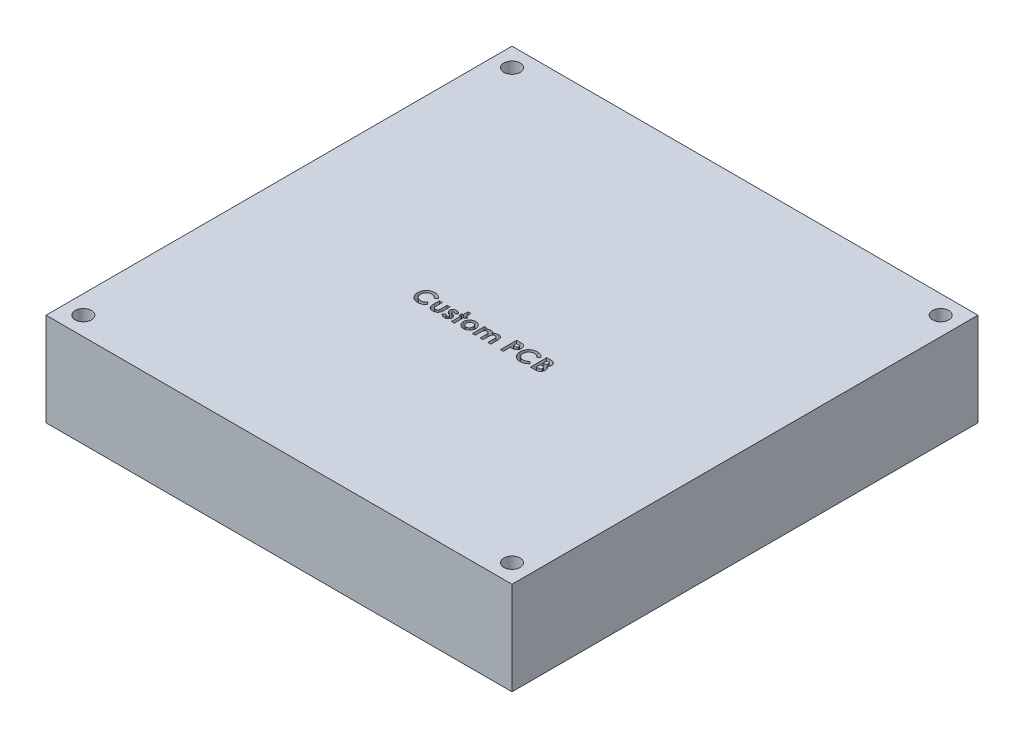
SolidWorks part; units mm, degrees
ref_plane "Front Plane" through (0, 0, 0) normal (0, 0, 1) x (1, 0, 0)
ref_plane "Top Plane" through (0, 0, 0) normal (0, 1, 0) x (1, 0, 0)
ref_plane "Right Plane" through (0, 0, 0) normal (1, 0, 0) x (0, 0, -1)
sketch "Sketch1" plane through (0, 0, 0) normal (0, 1, 0) x (1, 0, 0)
  line L1 (-100, 100) -> (0, 100)
  line L2 (-100, 100) -> (-100, 0)
  line L3 (-100, 0) -> (0, 0)
  line L4 (0, 100) -> (0, 0)
  circle A0 centre (-96, 96) radius 1.75
  circle A1 centre (-96, 4) radius 1.75
  circle A2 centre (-4, 4) radius 1.75
  circle A3 centre (-4, 96) radius 1.75
  dimension "D3" = 3.5
  dimension "D1" = 100
  dimension "D2" = 100
  dimension "D4" = 4
  dimension "D5" = 4
  dimension "D6" = 4
  dimension "D7" = 4
  dimension "D8" = 4
  dimension "D9" = 4
  dimension "D10" = 4
  dimension "D11" = 4
extrude "Boss-Extrude1" add sketch "Sketch1" along normal blind 20
sketch "Sketch2" plane through (0, 20, 0) normal (0, 1, 0) x (1, 0, 0)
  line L0 (-100, 42.3341) -> (0, 42.3341) construction
  line L1 (-100, 100) -> (-100, 0) construction
  line L2 (0, -11) -> (0, 11) construction
  text T0 "<b>Custom PCB</b>"
extrude "Cut-Extrude1" cut sketch "Sketch2" against normal blind 2
